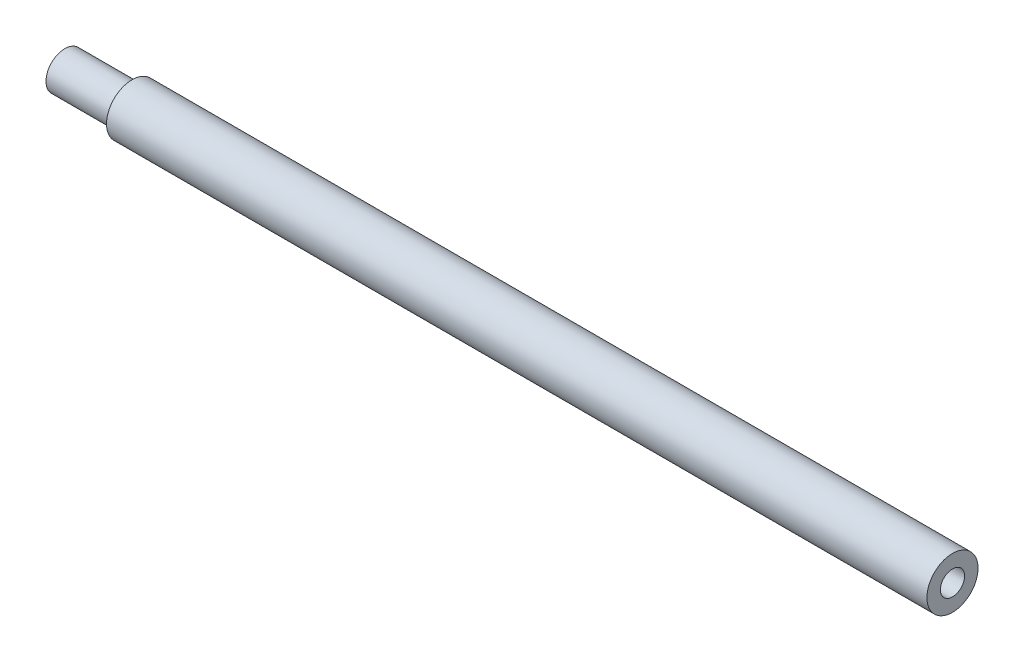
SolidWorks part; units mm, degrees
ref_plane "Front Plane" through (0, 0, 0) normal (0, 0, 1) x (1, 0, 0)
ref_plane "Top Plane" through (0, 0, 0) normal (0, 1, 0) x (1, 0, 0)
ref_plane "Right Plane" through (0, 0, 0) normal (1, 0, 0) x (0, 0, -1)
ref_axis "Axis1" through (-88.99, 0, 0) along (1, 0, 0)
sketch "Sketch1" plane through (0, 0, 0) normal (0, 0, 1) x (1, 0, 0)
  line L0 (0, -0.45) -> (33, -0.45)
  line L1 (33, -0.45) -> (33, -0.95)
  line L2 (33, -0.95) -> (2.5, -0.95)
  line L3 (2.5, -0.95) -> (2.5, -0.7)
  line L4 (2.5, -0.7) -> (0, -0.7)
  line L5 (0, -0.7) -> (0, -0.45)
  dimension "D1" = 0.45
  dimension "D2" = 0.25
  dimension "D3" = 0.25
  dimension "D4" = 2.5
  dimension "D5" = 33
revolve "Revolve1" add sketch "Sketch1" angle 360 about axis through (-88.99, 0, 0) along (1, 0, 0)
